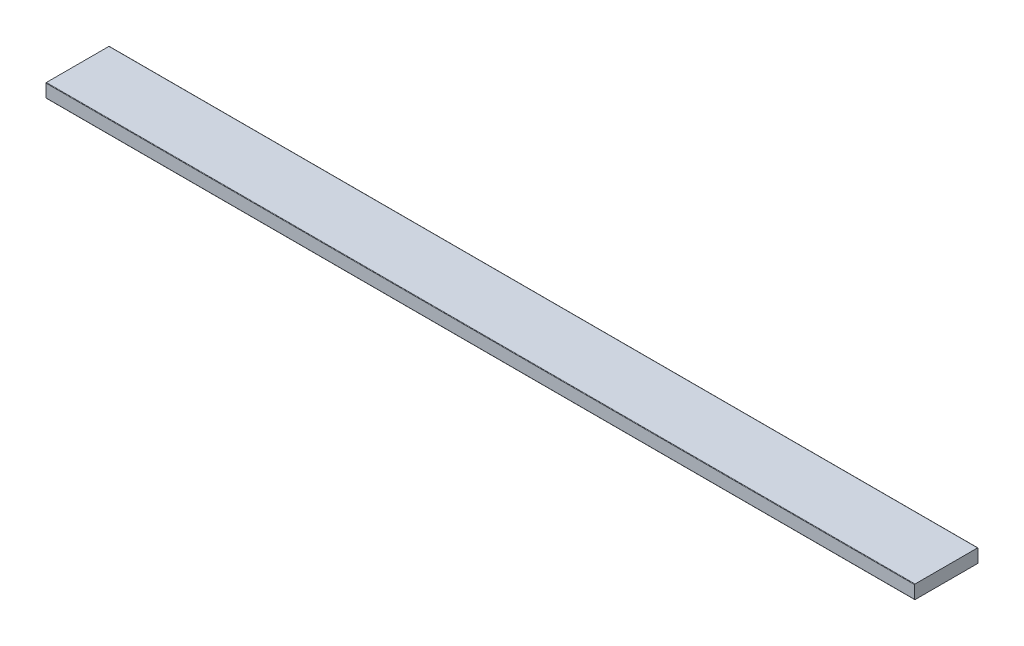
SolidWorks part; units mm, degrees
ref_plane "Front Plane" through (0, 0, 0) normal (0, 0, 1) x (1, 0, 0)
ref_plane "Top Plane" through (0, 0, 0) normal (0, 1, 0) x (1, 0, 0)
ref_plane "Right Plane" through (0, 0, 0) normal (1, 0, 0) x (0, 0, -1)
sketch "Sketch1" plane through (0, 0, 0) normal (0, 1, 0) x (1, 0, 0)
  line L1 (304.8, -22.225) -> (-304.8, -22.225)
  line L2 (304.8, -22.225) -> (304.8, 22.225)
  line L3 (304.8, 22.225) -> (-304.8, 22.225)
  line L4 (-304.8, -22.225) -> (-304.8, 22.225)
  line L5 (304.8, -22.225) -> (-304.8, 22.225) construction
  line L6 (304.8, 22.225) -> (-304.8, -22.225) construction
  point P0 (0, 0)
  dimension "Length" = 609.6
  dimension "Width" = 44.45
sketch "Sketch2" plane through (0, 0, 0) normal (1, 0, 0) x (0, 0, -1)
  line L0 (22.225, 4.7625) -> (22.225, -4.7625) construction
  point P2 (22.225, 0)
  dimension "Thickness" = 9.525
sketch "Sketch3" plane through (0, 0, 0) normal (0, 1, 0) x (1, 0, 0)
  line L1 (-304.8, 22.225) -> (304.8, 22.225)
  line L2 (-304.8, 22.225) -> (-304.8, -22.225)
  line L3 (-304.8, -22.225) -> (304.8, -22.225)
  line L4 (304.8, 22.225) -> (304.8, -22.225)
extrude "Boss-Extrude1" add sketch "Sketch3" against normal up to vertex (4.7625 mm away) and the other way up to vertex (4.7625 mm away) up to point (0, -4.7625, -22.225) other way up to point (0, 4.7625, -22.225)
fillet "Fillet1" radius 0.3143 4 edges at (0, -4.7625, 22.225) (0, -4.7625, -22.225) (0, 4.7625, -22.225) (0, 4.7625, 22.225)
equation "\"D1@Fillet1\" = \"Thickness@Sketch2\" * .033"
